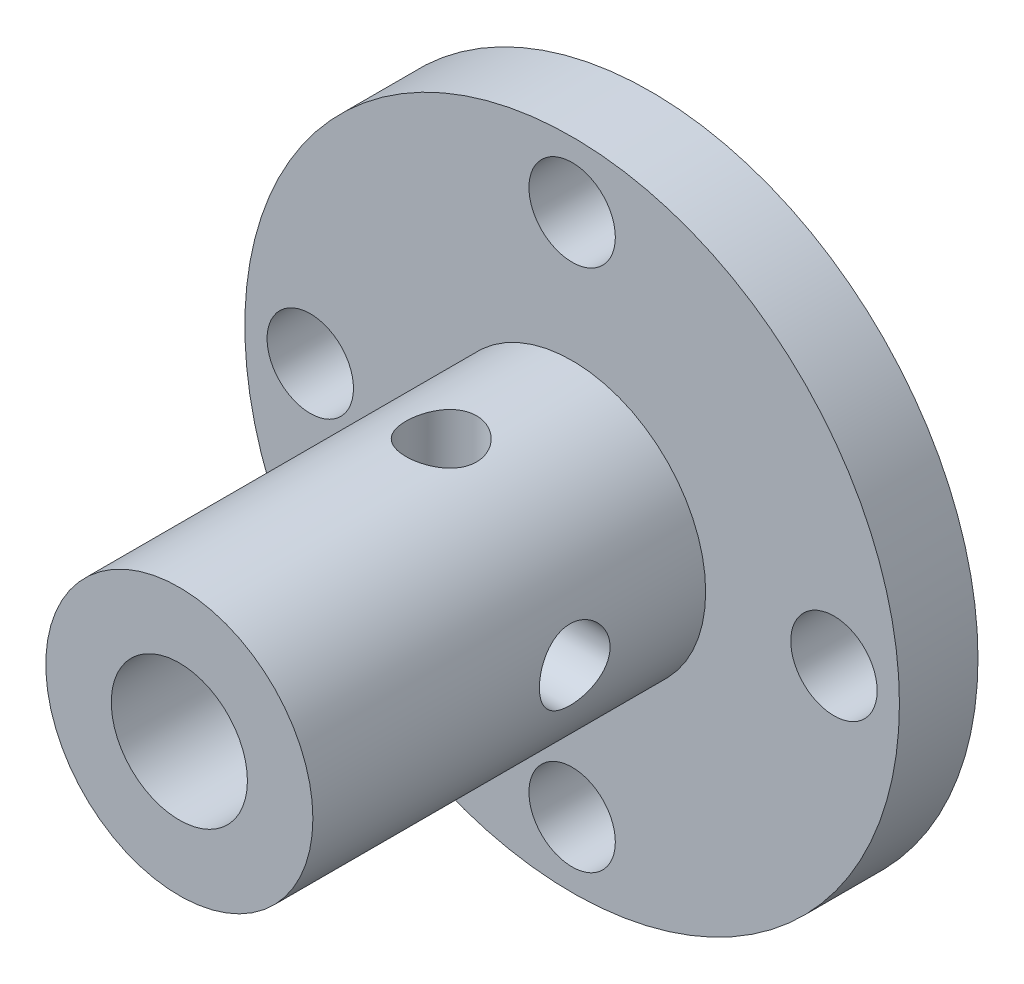
SolidWorks part; units mm, degrees
ref_plane "前视基准面" through (0, 0, 0) normal (0, 0, 1) x (1, 0, 0)
ref_plane "上视基准面" through (0, 0, 0) normal (0, 1, 0) x (1, 0, 0)
ref_plane "右视基准面" through (0, 0, 0) normal (1, 0, 0) x (0, 0, -1)
other "Configuration Table"
sketch "草图1" plane through (0, 0, 0) normal (0, 0, 1) x (1, 0, 0)
  circle A0 centre (0, 0) radius 2.6
  circle A1 centre (0, 0) radius 5.1
  dimension "D1" = 5.2
  dimension "D2" = 2.5
extrude "凸台-拉伸1" add sketch "草图1" along normal blind 15
sketch "草图2" plane through (0, 0, 0) normal (0, 1, 0) x (1, 0, 0)
  line L0 (-5.6, -5) -> (6.9112, -5) construction
  line L2 (0, 0) -> (0, -13.7076) construction
  circle A0 centre (0, -5) radius 1.35
  dimension "D1" = 2.7
  dimension "D2" = 5
extrude "切除-拉伸1" cut sketch "草图2" along normal through all both and the other way through all
sketch "草图3" plane through (0, 0, 0) normal (1, 0, 0) x (0, 0, -1)
  line L0 (-15, 0) -> (2.0624, 0) construction
  line L2 (-5, 5.8813) -> (-5, -5.4983) construction
  line L3 (0, -5.1) -> (0, 5.1) construction
  circle A0 centre (-5, 0) radius 1.35
  dimension "D2" = 2.7
  dimension "D1" = 5
extrude "切除-拉伸2" cut sketch "草图3" against normal through all both and the other way through all
sketch "草图4" plane through (0, 0, 0) normal (0, 0, 1) x (1, 0, 0)
  circle A0 centre (0, 0) radius 12.5
  circle A1 centre (0, -10) radius 1.65
  circle A2 centre (-10, 0) radius 1.65
  circle A3 centre (0, 10) radius 1.65
  circle A4 centre (10, 0) radius 1.65
  point P14 (0, 0)
  dimension "D1" = 25
  dimension "D2" = 3.3
  dimension "D3" = 10
  dimension "D4" = 4
extrude "凸台-拉伸2" add sketch "草图4" against normal blind 3
